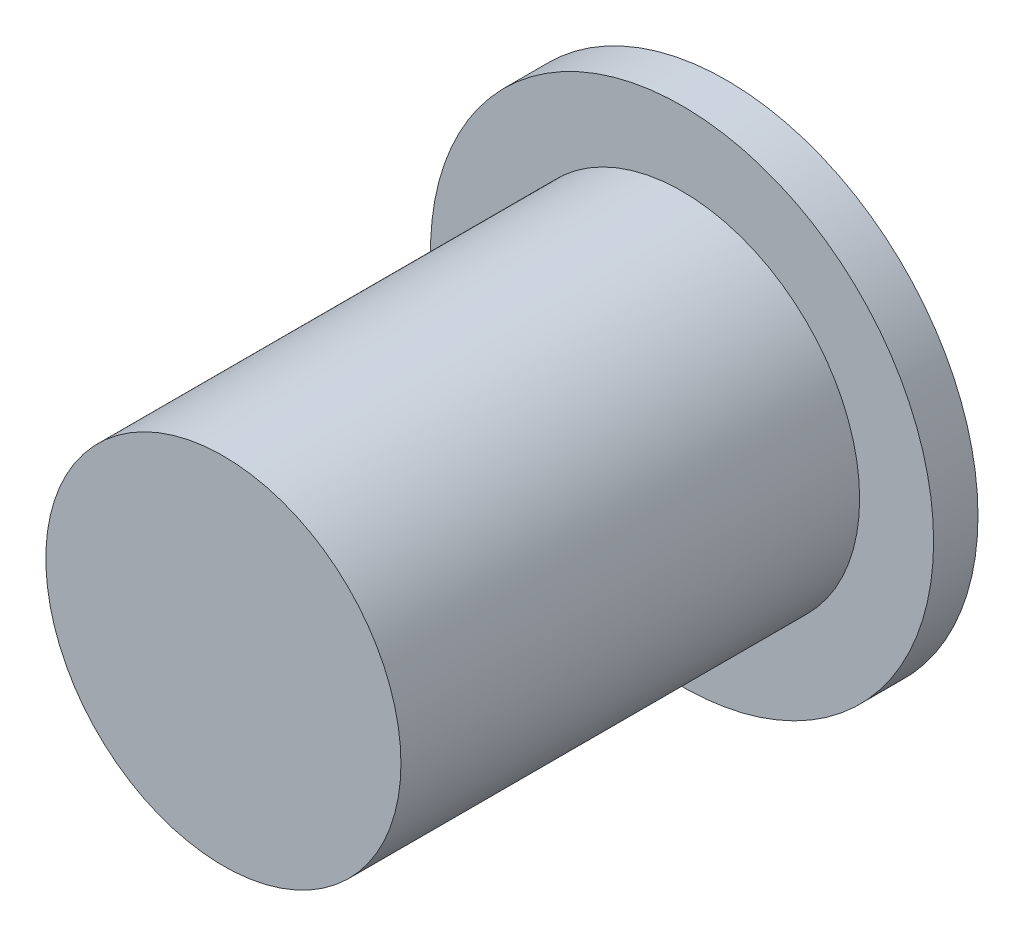
SolidWorks part; units mm, degrees
ref_plane "Front Plane" through (0, 0, 0) normal (0, 0, 1) x (1, 0, 0)
ref_plane "Top Plane" through (0, 0, 0) normal (0, 1, 0) x (1, 0, 0)
ref_plane "Right Plane" through (0, 0, 0) normal (1, 0, 0) x (0, 0, -1)
sketch "Sketch1" plane through (0, 0, 0) normal (0, 1, 0) x (1, 0, 0)
  line L0 (0, 0) -> (0, 34)
  line L1 (0, 34) -> (17, 34)
  line L2 (17, 34) -> (17, 31)
  line L3 (17, 31) -> (12, 31)
  line L4 (12, 31) -> (12, 0)
  line L5 (12, 0) -> (0, 0)
  dimension "D1" = 12
  dimension "D2" = 34
  dimension "D3" = 3
  dimension "D4" = 17
revolve "Revolve1" add sketch "Sketch1" angle 360 about L0
